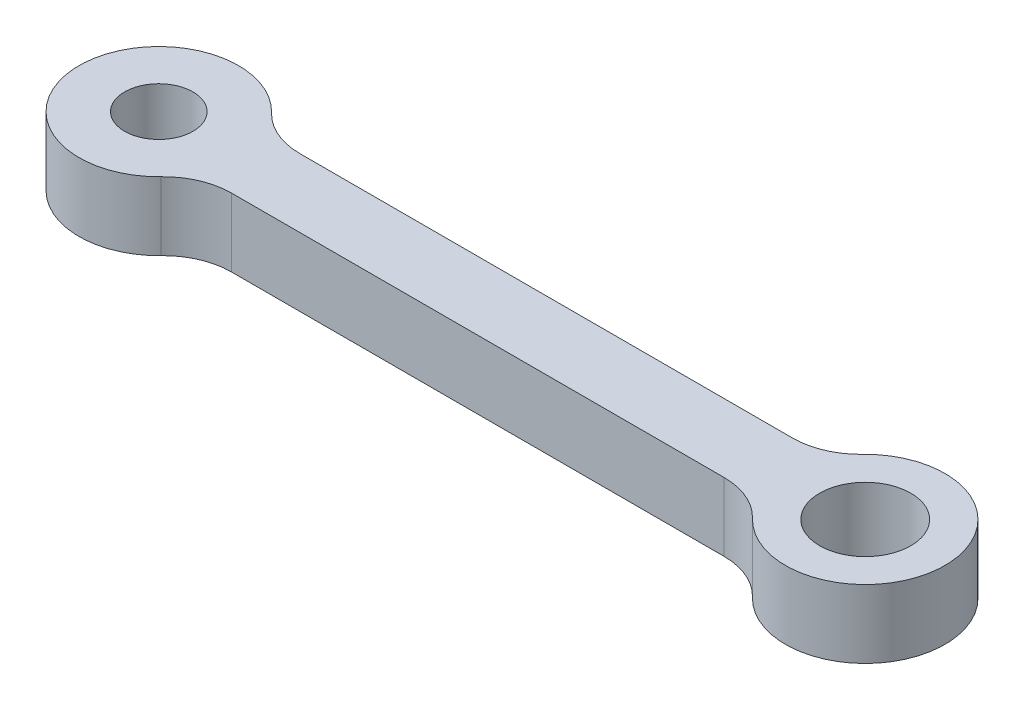
SolidWorks part; units mm, degrees
material "Vero PureWhite"
ref_plane "Front Plane" through (0, 0, 0) normal (0, 0, 1) x (1, 0, 0)
ref_plane "Top Plane" through (0, 0, 0) normal (0, 1, 0) x (1, 0, 0)
ref_plane "Right Plane" through (0, 0, 0) normal (1, 0, 0) x (0, 0, -1)
sketch "Sketch1" plane through (0, 0, 0) normal (0, 1, 0) x (1, 0, 0)
  line L0 (0, 0) -> (31, 0) construction
  line L1 (3.1623, 1.5) -> (27.8377, 1.5)
  line L2 (3.1623, -1.5) -> (27.8377, -1.5)
  circle A0 centre (0, 0) radius 3.5
  circle A1 centre (31, 0) radius 3.5
  circle A2 centre (0, 0) radius 1.5
  circle A3 centre (31, 0) radius 2
  dimension "D1" = 7
  dimension "D3" = 7
  dimension "D5" = 3
  dimension "D6" = 4
  dimension "D2" = 31
  dimension "D4" = 1.5
extrude "Boss-Extrude1" add sketch "Sketch1" along normal blind 3
fillet "Fillet1" radius 3 4 edges at (3.1623, 1.5, 1.5) (27.8377, 1.5, 1.5) (27.8377, 1.5, -1.5) (3.1623, 1.5, -1.5)
